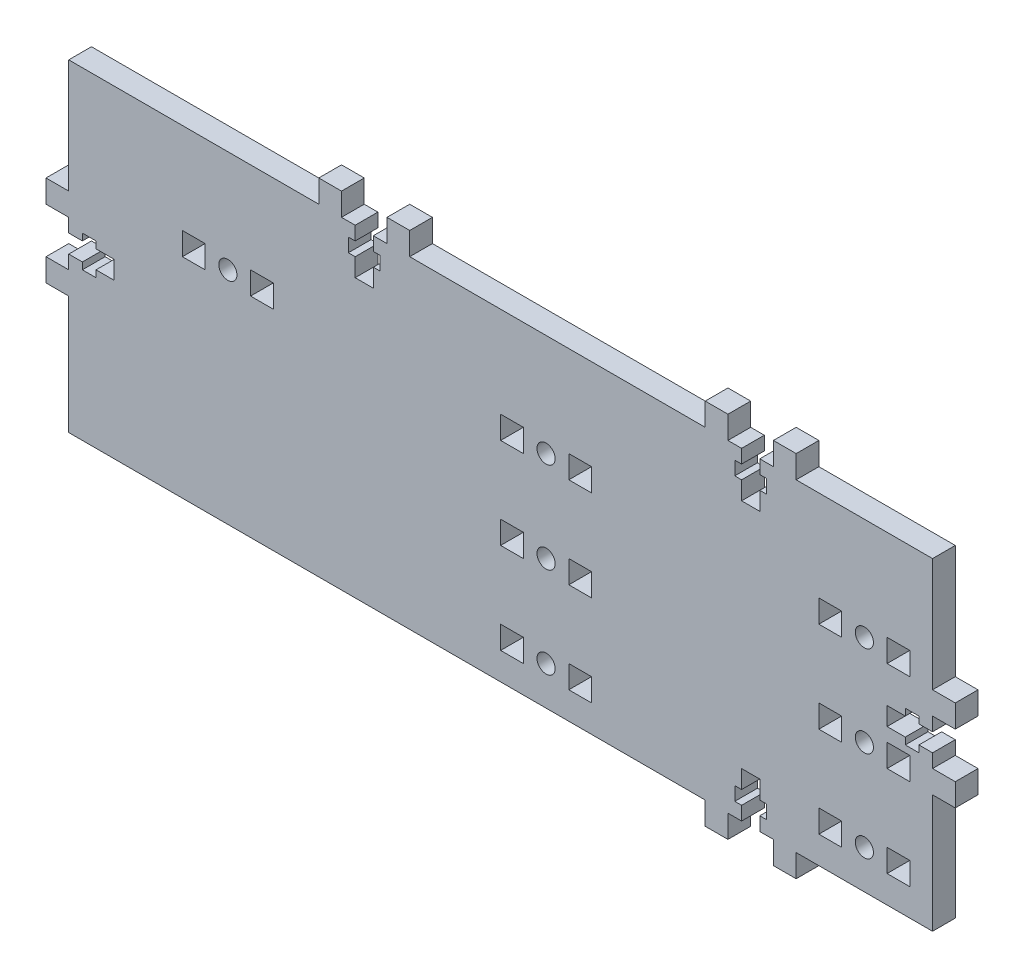
SolidWorks part; units mm, degrees
ref_plane "Plan de face" through (0, 0, 0) normal (0, 0, 1) x (1, 0, 0)
ref_plane "Plan de dessus" through (0, 0, 0) normal (0, 1, 0) x (1, 0, 0)
ref_plane "Plan de droite" through (0, 0, 0) normal (1, 0, 0) x (0, 0, -1)
sketch "Esquisse1" plane through (0, 0, 0) normal (0, 0, 1) x (1, 0, 0)
  line L0 (0, 0) -> (92.7082, 0) construction
  line L1 (0, -20) -> (92.7082, -20) construction
  line L2 (0, -40) -> (92.7082, -40) construction
  line L3 (85, -48.5) -> (85, 22.5) construction
  line L4 (85, 22.5) -> (-105, 22.5) construction
  line L5 (-105, 22.5) -> (-105, -48.5) construction
  line L7 (-105, -48.5) -> (85, -48.5) construction
  line L8 (-105, 22.5) -> (-50, 22.5)
  line L9 (-30, 22.5) -> (35, 22.5)
  line L10 (55, 22.5) -> (85, 22.5)
  line L11 (85, 22.5) -> (85, -2.5)
  line L12 (85, -22.5) -> (85, -48.5)
  line L13 (55, -48.5) -> (85, -48.5)
  line L14 (-105, -48.5) -> (35, -48.5)
  line L15 (-105, 22.5) -> (-105, -2.5)
  line L16 (-105, -22.5) -> (-105, -48.5)
  line B0 (-5, 0) -> (5, 0) construction
  line B1 (-5, 2.5) -> (-10, 2.5)
  line B2 (-5, 2.5) -> (-5, -2.5)
  line B3 (-5, -2.5) -> (-10, -2.5)
  line B4 (-10, 2.5) -> (-10, -2.5)
  line B5 (5, 2.5) -> (10, 2.5)
  line B6 (5, 2.5) -> (5, -2.5)
  line B7 (5, -2.5) -> (10, -2.5)
  line B8 (10, 2.5) -> (10, -2.5)
  line B9 (0, 0) -> (0, 6.9724) construction
  circle B10 centre (0, 0) radius 2
  line B11 (65, 0) -> (75, 0) construction
  line B12 (65, 2.5) -> (60, 2.5)
  line B13 (65, 2.5) -> (65, -2.5)
  line B14 (65, -2.5) -> (60, -2.5)
  line B15 (60, 2.5) -> (60, -2.5)
  line B16 (75, 2.5) -> (80, 2.5)
  line B17 (75, 2.5) -> (75, -2.5)
  line B18 (75, -2.5) -> (80, -2.5)
  line B19 (80, 2.5) -> (80, -2.5)
  line B20 (70, 0) -> (70, 6.9724) construction
  circle B21 centre (70, 0) radius 2
  line B22 (-5, -20) -> (5, -20) construction
  line B23 (-5, -17.5) -> (-10, -17.5)
  line B24 (-5, -17.5) -> (-5, -22.5)
  line B25 (-5, -22.5) -> (-10, -22.5)
  line B26 (-10, -17.5) -> (-10, -22.5)
  line B27 (5, -17.5) -> (10, -17.5)
  line B28 (5, -17.5) -> (5, -22.5)
  line B29 (5, -22.5) -> (10, -22.5)
  line B30 (10, -17.5) -> (10, -22.5)
  line B31 (0, -20) -> (0, -13.0276) construction
  circle B32 centre (0, -20) radius 2
  line B33 (65, -20) -> (75, -20) construction
  line B34 (65, -17.5) -> (60, -17.5)
  line B35 (65, -17.5) -> (65, -22.5)
  line B36 (65, -22.5) -> (60, -22.5)
  line B37 (60, -17.5) -> (60, -22.5)
  line B38 (75, -17.5) -> (80, -17.5)
  line B39 (75, -17.5) -> (75, -22.5)
  line B40 (75, -22.5) -> (80, -22.5)
  line B41 (80, -17.5) -> (80, -22.5)
  line B42 (70, -20) -> (70, -13.0276) construction
  circle B43 centre (70, -20) radius 2
  line B44 (-5, -40) -> (5, -40) construction
  line B45 (-5, -37.5) -> (-10, -37.5)
  line B46 (-5, -37.5) -> (-5, -42.5)
  line B47 (-5, -42.5) -> (-10, -42.5)
  line B48 (-10, -37.5) -> (-10, -42.5)
  line B49 (5, -37.5) -> (10, -37.5)
  line B50 (5, -37.5) -> (5, -42.5)
  line B51 (5, -42.5) -> (10, -42.5)
  line B52 (10, -37.5) -> (10, -42.5)
  line B53 (0, -40) -> (0, -33.0276) construction
  circle B54 centre (0, -40) radius 2
  line B55 (65, -40) -> (75, -40) construction
  line B56 (65, -37.5) -> (60, -37.5)
  line B57 (65, -37.5) -> (65, -42.5)
  line B58 (65, -42.5) -> (60, -42.5)
  line B59 (60, -37.5) -> (60, -42.5)
  line B60 (75, -37.5) -> (80, -37.5)
  line B61 (75, -37.5) -> (75, -42.5)
  line B62 (75, -42.5) -> (80, -42.5)
  line B63 (80, -37.5) -> (80, -42.5)
  line B64 (70, -40) -> (70, -33.0276) construction
  circle B65 centre (70, -40) radius 2
  line B66 (-75, 0) -> (-65, 0) construction
  line B67 (-75, 2.5) -> (-80, 2.5)
  line B68 (-75, 2.5) -> (-75, -2.5)
  line B69 (-75, -2.5) -> (-80, -2.5)
  line B70 (-80, 2.5) -> (-80, -2.5)
  line B71 (-65, 2.5) -> (-60, 2.5)
  line B72 (-65, 2.5) -> (-65, -2.5)
  line B73 (-65, -2.5) -> (-60, -2.5)
  line B74 (-60, 2.5) -> (-60, -2.5)
  line B75 (-70, 0) -> (-70, 6.9724) construction
  circle B76 centre (-70, 0) radius 2
  line B77 (-36.5, 19.5) -> (-36.5, 16.5)
  line B78 (-42, 16.5) -> (-42, 12.5)
  line B79 (-38, 12.5) -> (-38, 16.5)
  line B80 (-36.5, 16.5) -> (-38, 16.5)
  line B81 (-40, 22.5) -> (-40, 11.2792) construction
  line B82 (-38, 22.5) -> (-35, 22.5)
  line B83 (-35, 27.5) -> (-30, 27.5)
  line B84 (-30, 27.5) -> (-30, 22.5)
  line B85 (-35, 27.5) -> (-35, 22.5)
  line B86 (-42, 22.5) -> (-45, 22.5)
  line B87 (-45, 22.5) -> (-45, 27.5)
  line B88 (-45, 27.5) -> (-50, 27.5)
  line B89 (-50, 27.5) -> (-50, 22.5)
  line B90 (-38, 22.5) -> (-42, 22.5) construction
  line B91 (-42, 22.5) -> (-42, 19.5)
  line B92 (-42, 16.5) -> (-43.5, 16.5)
  line B93 (-43.5, 19.5) -> (-42, 19.5)
  line B94 (-42, 12.5) -> (-38, 12.5)
  line B95 (-38, 19.5) -> (-36.5, 19.5)
  line B96 (-43.5, 16.5) -> (-43.5, 19.5)
  line B97 (-38, 19.5) -> (-38, 22.5)
  line B98 (-40, 12.5) -> (-40, 22.5) construction
  line B99 (48.5, 19.5) -> (48.5, 16.5)
  line B100 (43, 16.5) -> (43, 12.5)
  line B101 (47, 12.5) -> (47, 16.5)
  line B102 (48.5, 16.5) -> (47, 16.5)
  line B103 (45, 22.5) -> (45, 11.2792) construction
  line B104 (47, 22.5) -> (50, 22.5)
  line B105 (50, 27.5) -> (55, 27.5)
  line B106 (55, 27.5) -> (55, 22.5)
  line B107 (50, 27.5) -> (50, 22.5)
  line B108 (43, 22.5) -> (40, 22.5)
  line B109 (40, 22.5) -> (40, 27.5)
  line B110 (40, 27.5) -> (35, 27.5)
  line B111 (35, 27.5) -> (35, 22.5)
  line B112 (47, 22.5) -> (43, 22.5) construction
  line B113 (43, 22.5) -> (43, 19.5)
  line B114 (43, 16.5) -> (41.5, 16.5)
  line B115 (41.5, 19.5) -> (43, 19.5)
  line B116 (43, 12.5) -> (47, 12.5)
  line B117 (47, 19.5) -> (48.5, 19.5)
  line B118 (41.5, 16.5) -> (41.5, 19.5)
  line B119 (47, 19.5) -> (47, 22.5)
  line B120 (45, 12.5) -> (45, 22.5) construction
  line B121 (82, -16) -> (79, -16)
  line B122 (79, -10.5) -> (75, -10.5)
  line B123 (75, -14.5) -> (79, -14.5)
  line B124 (79, -16) -> (79, -14.5)
  line B125 (85, -12.5) -> (73.7792, -12.5) construction
  line B126 (85, -14.5) -> (85, -17.5)
  line B127 (90, -17.5) -> (90, -22.5)
  line B128 (90, -22.5) -> (85, -22.5)
  line B129 (90, -17.5) -> (85, -17.5)
  line B130 (85, -10.5) -> (85, -7.5)
  line B131 (85, -7.5) -> (90, -7.5)
  line B132 (90, -7.5) -> (90, -2.5)
  line B133 (90, -2.5) -> (85, -2.5)
  line B134 (85, -14.5) -> (85, -10.5) construction
  line B135 (85, -10.5) -> (82, -10.5)
  line B136 (79, -10.5) -> (79, -9)
  line B137 (82, -9) -> (82, -10.5)
  line B138 (75, -10.5) -> (75, -14.5)
  line B139 (82, -14.5) -> (82, -16)
  line B140 (79, -9) -> (82, -9)
  line B141 (82, -14.5) -> (85, -14.5)
  line B142 (75, -12.5) -> (85, -12.5) construction
  line B143 (41.5, -45.5) -> (41.5, -42.5)
  line B144 (47, -42.5) -> (47, -38.5)
  line B145 (43, -38.5) -> (43, -42.5)
  line B146 (41.5, -42.5) -> (43, -42.5)
  line B147 (45, -48.5) -> (45, -37.2792) construction
  line B148 (43, -48.5) -> (40, -48.5)
  line B149 (40, -53.5) -> (35, -53.5)
  line B150 (35, -53.5) -> (35, -48.5)
  line B151 (40, -53.5) -> (40, -48.5)
  line B152 (47, -48.5) -> (50, -48.5)
  line B153 (50, -48.5) -> (50, -53.5)
  line B154 (50, -53.5) -> (55, -53.5)
  line B155 (55, -53.5) -> (55, -48.5)
  line B156 (43, -48.5) -> (47, -48.5) construction
  line B157 (47, -48.5) -> (47, -45.5)
  line B158 (47, -42.5) -> (48.5, -42.5)
  line B159 (48.5, -45.5) -> (47, -45.5)
  line B160 (47, -38.5) -> (43, -38.5)
  line B161 (43, -45.5) -> (41.5, -45.5)
  line B162 (48.5, -42.5) -> (48.5, -45.5)
  line B163 (43, -45.5) -> (43, -48.5)
  line B164 (45, -38.5) -> (45, -48.5) construction
  line B165 (-102, -9) -> (-99, -9)
  line B166 (-99, -14.5) -> (-95, -14.5)
  line B167 (-95, -10.5) -> (-99, -10.5)
  line B168 (-99, -9) -> (-99, -10.5)
  line B169 (-105, -12.5) -> (-93.7792, -12.5) construction
  line B170 (-105, -10.5) -> (-105, -7.5)
  line B171 (-110, -7.5) -> (-110, -2.5)
  line B172 (-110, -2.5) -> (-105, -2.5)
  line B173 (-110, -7.5) -> (-105, -7.5)
  line B174 (-105, -14.5) -> (-105, -17.5)
  line B175 (-105, -17.5) -> (-110, -17.5)
  line B176 (-110, -17.5) -> (-110, -22.5)
  line B177 (-110, -22.5) -> (-105, -22.5)
  line B178 (-105, -10.5) -> (-105, -14.5) construction
  line B179 (-105, -14.5) -> (-102, -14.5)
  line B180 (-99, -14.5) -> (-99, -16)
  line B181 (-102, -16) -> (-102, -14.5)
  line B182 (-95, -14.5) -> (-95, -10.5)
  line B183 (-102, -10.5) -> (-102, -9)
  line B184 (-99, -16) -> (-102, -16)
  line B185 (-102, -10.5) -> (-105, -10.5)
  line B186 (-95, -12.5) -> (-105, -12.5) construction
  dimension "D1" = 70
  dimension "D2" = 20
  dimension "D3" = 20
  dimension "D4" = 70
  dimension "D5" = 85
  dimension "D6" = 15
  dimension "D7" = 6
  dimension "D8" = 20
  dimension "D9" = 40
  dimension "D10" = 190
  dimension "D13" = 35
  dimension "D14" = 40
sketch_block_instance "Trou M4 plots 5mm-1"
sketch_block "Trou M4 plots 5mm" parameters "D2"=4, "D1"=5, "D3"=5, "D4"=10
sketch_block_instance "Trou M4 plots 5mm-2"
sketch_block_instance "Trou M4 plots 5mm-4"
sketch_block_instance "Trou M4 plots 5mm-5"
sketch_block_instance "Trou M4 plots 5mm-6"
sketch_block_instance "Trou M4 plots 5mm-7"
sketch_block_instance "Trou M4 plots 5mm-8"
sketch_block_instance "Insert M4 plots ep 5mm-1"
sketch_block "Insert M4 plots ep 5mm" parameters "D1"=10, "D2"=5, "D3"=5, "D4"=7, "D5"=4, "D6"=3, "D7"=3, "D8"=10
sketch_block_instance "Insert M4 plots ep 5mm-3"
sketch_block_instance "Insert M4 plots ep 5mm-4"
sketch_block_instance "Insert M4 plots ep 5mm-5"
sketch_block_instance "Insert M4 plots ep 5mm-6"
extrude "Boss.-Extru.1" add sketch "Esquisse1" along normal blind 5
